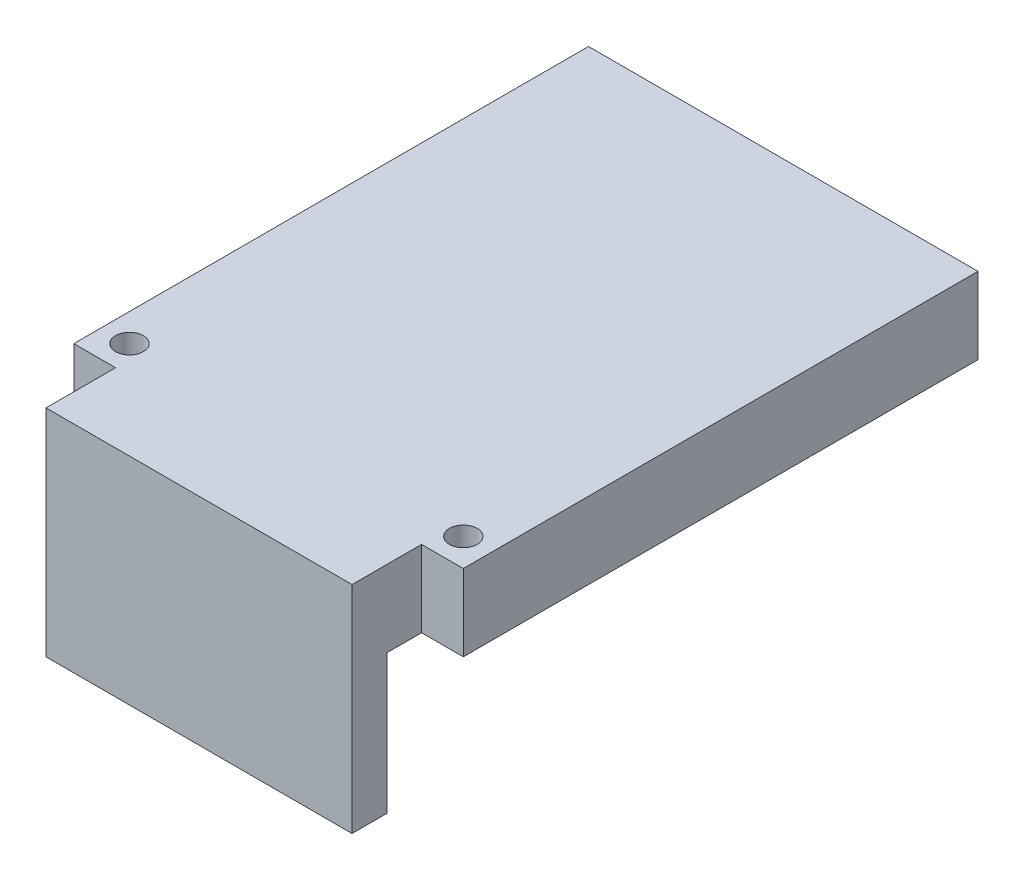
SolidWorks part; units mm, degrees
ref_plane "Front Plane" through (0, 0, 0) normal (0, 0, 1) x (1, 0, 0)
ref_plane "Top Plane" through (0, 0, 0) normal (0, 1, 0) x (1, 0, 0)
ref_plane "Right Plane" through (0, 0, 0) normal (1, 0, 0) x (0, 0, -1)
sketch "Sketch2" plane through (0, 0, 0) normal (0, 1, 0) x (1, 0, 0)
  line L1 (0, 0) -> (28, 0)
  line L2 (0, 0) -> (0, 42)
  line L3 (0, 42) -> (28, 42)
  line L4 (28, 0) -> (28, 42)
  dimension "D1" = 28
  dimension "D2" = 42
extrude "Boss-Extrude1" add sketch "Sketch2" along normal blind 5.5
sketch "Sketch3" plane through (0, 5.5, 0) normal (0, 1, 0) x (1, 0, 0)
  line L1 (0, 0) -> (3, 0)
  line L2 (0, 0) -> (0, 5)
  line L3 (0, 5) -> (3, 5)
  line L4 (3, 0) -> (3, 5)
  line L5 (28, 0) -> (25, 0)
  line L6 (28, 0) -> (28, 5)
  line L7 (28, 5) -> (25, 5)
  line L8 (25, 0) -> (25, 5)
  dimension "D1" = 3
  dimension "D2" = 5
  dimension "D3" = 5
  dimension "D4" = 3
extrude "Cut-Extrude1" cut sketch "Sketch3" against normal blind 5.5
sketch "Sketch4" plane through (0, 0, 0) normal (0, -1, 0) x (1, 0, 0)
  line L0 (3, 0) -> (3, -5) construction
  line L1 (3, -2.5) -> (25, -2.5)
  line L2 (3, -2.5) -> (3, 0)
  line L3 (3, 0) -> (25, 0)
  line L4 (25, -2.5) -> (25, 0)
  dimension "D1" = 2.5
extrude "Boss-Extrude2" add sketch "Sketch4" along normal blind 10
sketch "Sketch5" plane through (0, 5.5, 0) normal (0, 1, 0) x (1, 0, 0)
  line L0 (0, 42) -> (0, 5) construction
  line L1 (3, 5) -> (0, 5) construction
  line L2 (28, 5) -> (28, 42) construction
  line L3 (28, 5) -> (25, 5) construction
  circle A0 centre (2, 7) radius 1
  circle A1 centre (26, 7) radius 1
  dimension "D1" = 2
  dimension "D2" = 2
  dimension "D3" = 2
  dimension "D4" = 2
  dimension "D5" = 2
  dimension "D6" = 2
extrude "Cut-Extrude2" cut sketch "Sketch5" against normal blind 10
ref_plane "Plane1" through (3, 5.5, -5) normal (-1, 0, 0) x (0, 0, 1)
